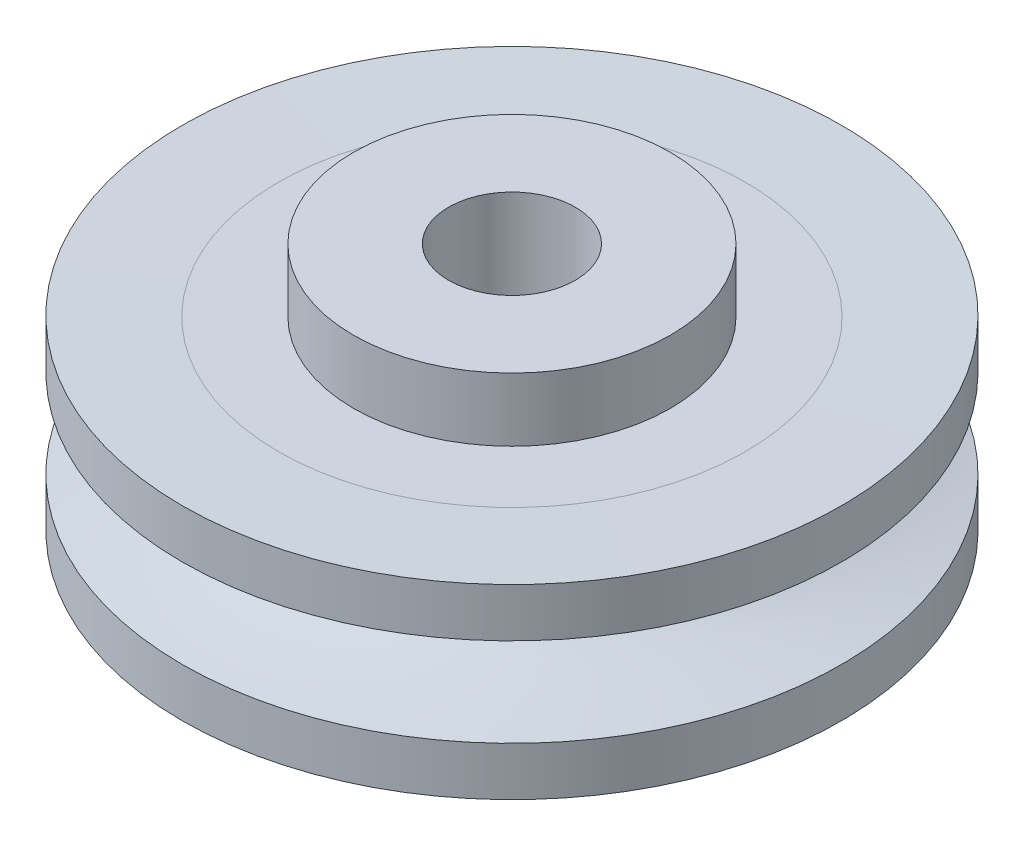
SolidWorks part; units mm, degrees
ref_plane "前视基准面" through (0, 0, 0) normal (0, 0, 1) x (1, 0, 0)
ref_plane "上视基准面" through (0, 0, 0) normal (0, 1, 0) x (1, 0, 0)
ref_plane "右视基准面" through (0, 0, 0) normal (1, 0, 0) x (0, 0, -1)
sketch "草图1" plane through (0, 0, 0) normal (0, 0, 1) x (1, 0, 0)
  line L0 (0, 2.0786) -> (0, -2.1269) construction
  line L1 (2.5, -1.45) -> (3.6831, -1.45)
  line L2 (1, 0) -> (5.8123, 0) construction
  line L3 (1, 2.45) -> (1, -2.45)
  line L4 (2.5, -2.45) -> (2.5, -1.45)
  line L5 (5.2, 1.4695) -> (5.2, 0.7)
  line L6 (1, -2.45) -> (2.5, -2.45)
  line L7 (3.6831, -1.45) -> (5.2, -1.4695)
  line L8 (3.6831, 1.45) -> (5.2, 1.4695)
  line L9 (5.2, -1.4695) -> (5.2, -0.7)
  line L11 (1, 2.45) -> (2.5, 2.45)
  line L12 (2.5, 2.45) -> (2.5, 1.45)
  line L13 (2.5, 1.45) -> (3.6831, 1.45)
  conic Q0 (5.2, 0.7) -> (5.2, -0.7) control (2.0752, 0) rho 0.51203
  point P14 (0, 2)
  dimension "D1" = 1
  dimension "D2" = 4.2
  dimension "D3" = 2.45
  dimension "D4" = 1.4
  dimension "D5" = 1.5
  dimension "D6" = 1.6
revolve "旋转9" add sketch "草图1" angle 360 about L0
